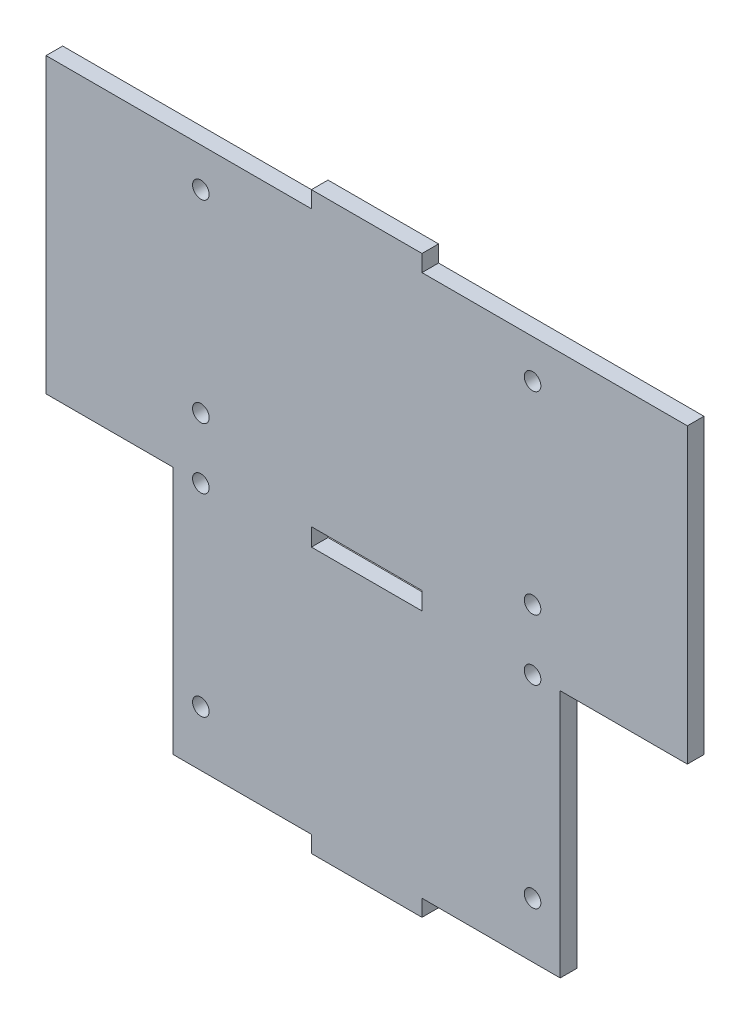
SolidWorks part; units mm, degrees
material "Maple"
ref_plane "Front Plane" through (0, 0, 0) normal (0, 0, 1) x (1, 0, 0)
ref_plane "Top Plane" through (0, 0, 0) normal (0, 1, 0) x (1, 0, 0)
ref_plane "Right Plane" through (0, 0, 0) normal (1, 0, 0) x (0, 0, -1)
sketch "Sketch1" plane through (0, 0, 0) normal (0, 0, 1) x (1, 0, 0)
  line L0 (10, -48) -> (-10, -48)
  line L1 (-10, -48) -> (-10, -45)
  line L2 (-10, -45) -> (-35, -45)
  line L4 (-58, 53) -> (-10, 53)
  line L5 (-10, 53) -> (-10, 56)
  line L6 (-10, 56) -> (10, 56)
  line L7 (10, 56) -> (10, 53)
  line L8 (10, 53) -> (58, 53)
  line L10 (35, -45) -> (10, -45)
  line L11 (10, -45) -> (10, -48)
  line L12 (-30, 46) -> (-30, 11) construction
  line L13 (-30, 11) -> (30, 11) construction
  line L14 (30, 11) -> (30, 46) construction
  line L15 (30, 46) -> (-30, 46) construction
  line L16 (-30, 0) -> (-30, -35) construction
  line L17 (-30, -35) -> (30, -35) construction
  line L18 (30, -35) -> (30, 0) construction
  line L19 (30, 0) -> (-30, 0) construction
  line L20 (-35, -45) -> (-35, 0)
  line L21 (-10, 3.2) -> (10, 3.2)
  line L22 (-10, 3.2) -> (-10, 0)
  line L23 (-10, 0) -> (10, 0)
  line L24 (10, 3.2) -> (10, 0)
  line L25 (-10, 3.2) -> (10, 0) construction
  line L26 (-10, 0) -> (10, 3.2) construction
  line L27 (-35, 0) -> (-58, 0)
  line L29 (35, -45) -> (35, 0)
  line L30 (35, 0) -> (58, 0)
  line L32 (-58, 0) -> (-58, 53)
  line L35 (58, 0) -> (58, 53)
  circle A0 centre (-30, 0) radius 1.5
  circle A1 centre (-30, -35) radius 1.5
  circle A2 centre (30, 0) radius 1.5
  circle A3 centre (30, -35) radius 1.5
  circle A4 centre (-30, 11) radius 1.5
  circle A5 centre (-30, 46) radius 1.5
  circle A6 centre (30, 46) radius 1.5
  circle A7 centre (30, 11) radius 1.5
  point P12 (0, 56)
  point P31 (0, -35)
  point P32 (0, 1.6)
  dimension "D5" = 3
  dimension "D12" = 3.2
  dimension "D1" = 3
  dimension "D2" = 98
  dimension "D3" = 20
  dimension "D4" = 70
  dimension "D6" = 35
  dimension "D7" = 10
  dimension "D8" = 10
  dimension "D9" = 60
  dimension "D10" = 20
  dimension "D11" = 45
  dimension "D13" = 116
extrude "Boss-Extrude1" add sketch "Sketch1" along normal blind 3
